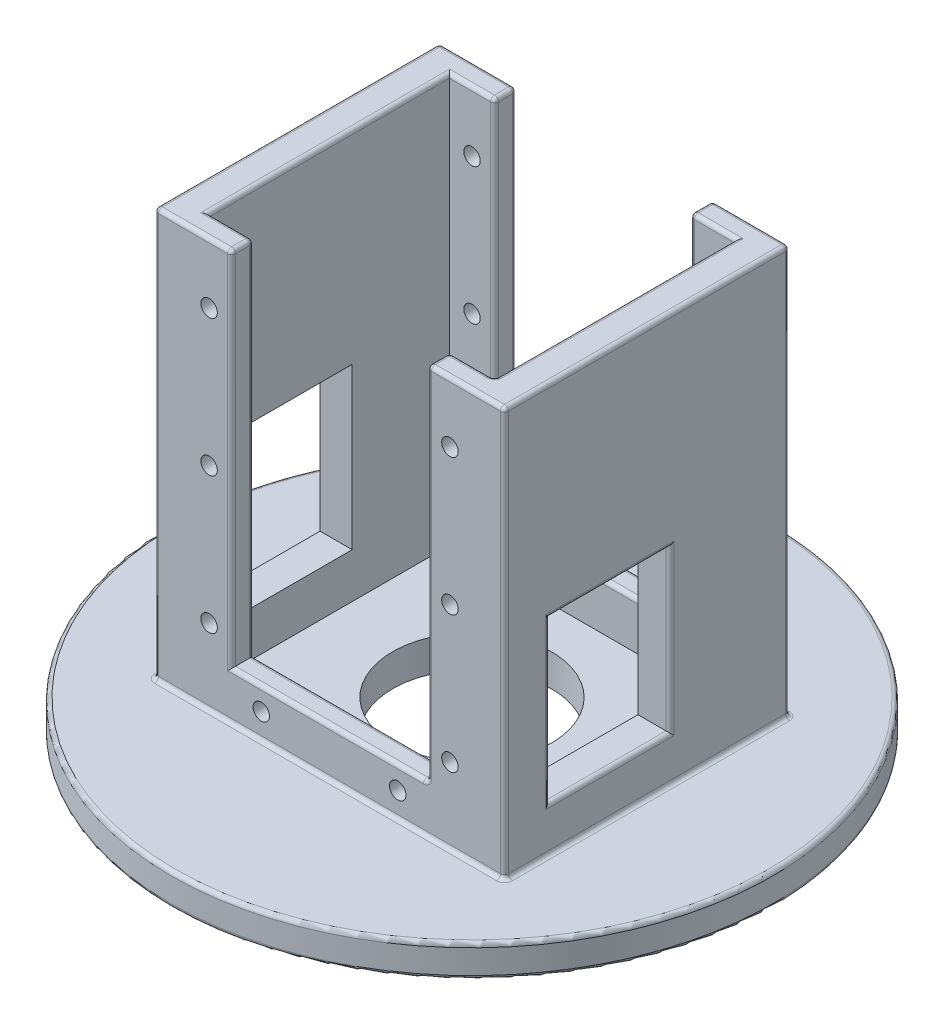
SolidWorks part; units mm, degrees
ref_plane "Front Plane" through (0, 0, 0) normal (0, 0, 1) x (1, 0, 0)
ref_plane "Top Plane" through (0, 0, 0) normal (0, 1, 0) x (1, 0, 0)
ref_plane "Right Plane" through (0, 0, 0) normal (1, 0, 0) x (0, 0, -1)
sketch "Sketch1" plane through (0, -34.7869, 0) normal (0, 1, 0) x (1, 0, 0)
  circle A0 centre (0, 0) radius 37.5
  dimension "D1" = 75
extrude "Boss-Extrude1" add sketch "Sketch1" along normal blind 4
sketch "Sketch2" plane through (-36.0045, -30.7869, 0) normal (0, 1, 0) x (1, 0, 0)
  circle A9 centre (36.0045, 0) radius 9.8792
extrude "Cut-Extrude1" cut sketch "Sketch2" against normal through all
ref_plane "Plane1" through (17.8, 0, 0) normal (1, 0, 0) x (0, 0, -1)
sketch "Sketch3" plane through (17.8, 0, 0) normal (1, 0, 0) x (0, 0, -1)
  line L0 (-17.25, 20.104) -> (-14.5, 20.104) construction
  line L1 (-15, 20.104) -> (15, 20.104)
  line L2 (-15, 20.104) -> (-15, -30.7869)
  line L3 (-15, -30.7869) -> (15, -30.7869)
  line L4 (15, 20.104) -> (15, -30.7869)
  line L5 (37.5, -30.7869) -> (-37.5, -30.7869) construction
  line L6 (15, -30.496) -> (15, -29.4389) construction
  line L7 (-15, 19.604) -> (-15, 18.7231) construction
extrude "Boss-Extrude2" add sketch "Sketch3" along normal blind 4
sketch "Sketch4" plane through (21.8, 0, 0) normal (1, 0, 0) x (0, 0, -1)
  line L0 (37.5, -30.7869) -> (-37.5, -30.7869) construction
  line L1 (-15, 20.104) -> (-17.75, 20.104)
  line L2 (-15, 20.104) -> (-15, -30.7869)
  line L3 (-15, -30.7869) -> (-17.75, -30.7869)
  line L4 (-17.75, 20.104) -> (-17.75, -30.7869)
  line L5 (-17.75, -21.896) -> (-17.75, 17.104) construction
  line L7 (15, 20.104) -> (17.75, 20.104)
  line L8 (15, 20.104) -> (15, -30.7869)
  line L9 (15, -30.7869) -> (17.75, -30.7869)
  line L10 (17.75, 20.104) -> (17.75, -30.7869)
  line L11 (15, -30.7869) -> (15, 20.104) construction
  line L12 (15, 20.104) -> (-15, 20.104) construction
  line L13 (-15, -30.7869) -> (15, -30.7869) construction
  line L14 (17.75, 13.603) -> (17.75, -18.395) construction
extrude "Boss-Extrude3" add sketch "Sketch4" against normal up to surface (9.6 mm away)
ref_plane "Plane2" through (-17.8, 0, 0) normal (-1, 0, 0) x (0, 0, 1)
sketch "Sketch5" plane through (-17.8, 0, 0) normal (-1, 0, 0) x (0, 0, 1)
  line L1 (-15, 20.104) -> (15, 20.104)
  line L2 (-15, 20.104) -> (-15, -30.7869)
  line L3 (-15, -30.7869) -> (15, -30.7869)
  line L4 (15, 20.104) -> (15, -30.7869)
extrude "Boss-Extrude4" add sketch "Sketch5" along normal blind 4
sketch "Sketch6" plane through (-21.8, 0, 0) normal (-1, 0, 0) x (0, 0, 1)
  line L1 (-15, 20.104) -> (-17.75, 20.104)
  line L2 (-15, 20.104) -> (-15, -30.7869)
  line L3 (-15, -30.7869) -> (-17.75, -30.7869)
  line L4 (-17.75, 20.104) -> (-17.75, -30.7869)
  line L5 (15, 20.104) -> (17.75, 20.104)
  line L6 (15, 20.104) -> (15, -30.7869)
  line L7 (15, -30.7869) -> (17.75, -30.7869)
  line L8 (17.75, 20.104) -> (17.75, -30.7869)
extrude "Boss-Extrude5" add sketch "Sketch6" against normal up to surface (9.6 mm away)
sketch "Sketch7" plane through (-36.0045, -30.7869, 0) normal (0, 1, 0) x (1, 0, 0)
  line L1 (48.2045, -15) -> (23.8045, -15)
  line L2 (48.2045, -15) -> (48.2045, -17.75)
  line L3 (48.2045, -17.75) -> (23.8045, -17.75)
  line L4 (23.8045, -15) -> (23.8045, -17.75)
  line L5 (23.8045, 15) -> (48.2045, 15)
  line L6 (23.8045, 15) -> (23.8045, 17.75)
  line L7 (23.8045, 17.75) -> (48.2045, 17.75)
  line L8 (48.2045, 15) -> (48.2045, 17.75)
extrude "Boss-Extrude6" add sketch "Sketch7" along normal up to surface (5.8909 mm away)
sketch "Sketch9" plane through (0, 0, 17.75) normal (0, 0, 1) x (1, 0, 0)
  circle A0 centre (-15, 12.604) radius 1.025
  circle A1 centre (-15, -4.396) radius 1.025
  circle A2 centre (-15, -21.396) radius 1.025
  circle A3 centre (-8.5, -27.696) radius 1.025
  circle A4 centre (8.5, -27.696) radius 1.025
  circle A5 centre (15, -21.396) radius 1.025
  circle A6 centre (15, -4.396) radius 1.025
  circle A7 centre (15, 12.604) radius 1.025
extrude "Cut-Extrude2" cut sketch "Sketch9" against normal through all
sketch "Sketch10" plane through (21.8, 0, 0) normal (1, 0, 0) x (0, 0, -1)
  line L1 (-12.1275, -5.1869) -> (2.8725, -5.1869)
  line L2 (-12.1275, -5.1869) -> (-12.1275, -25.1869)
  line L3 (-12.1275, -25.1869) -> (2.8725, -25.1869)
  line L4 (2.8725, -5.1869) -> (2.8725, -25.1869)
  dimension "D1" = 15
  dimension "D2" = 20
extrude "Cut-Extrude3" cut sketch "Sketch10" against normal through all
fillet "Fillet1" radius 0.5 46 edges at (0, -24.896, -15) (0, -24.896, 15) (0, -24.896, 17.75) (0, -30.7869, -17.75) (-12.2, -2.396, -15) (-12.2, -2.396, -17.75) (-12.2, -24.896, -16.375) (-15, 20.104, 15) (-12.2, 20.104, 16.375) (-17, 20.104, 17.75) (-17, 20.104, -17.75) (-12.2, 20.104, -16.375) (-15, 20.104, -15) (-17.8, 20.104, 0) (-21.8, -5.3414, 17.75) (-21.8, -30.7869, 0) (21.8, -30.7869, 0) (-21.8, -5.3414, -17.75) (21.8, 20.104, 0) (-21.8, 20.104, 0) (12.2, -2.396, -17.75) (12.2, -2.396, -15) (12.2, -24.896, -16.375) (12.2, -2.396, 15) (12.2, -2.396, 17.75) (12.2, -24.896, 16.375) (15, 20.104, -15) (12.2, 20.104, -16.375) (17, 20.104, -17.75) (17, 20.104, 17.75) (12.2, 20.104, 16.375) (15, 20.104, 15) (17.8, 20.104, 0) (21.8, -5.3414, -17.75) (21.8, -5.3414, 17.75) (21.8, -25.1869, 4.6275) (21.8, -15.1869, -2.8725) (21.8, -5.1869, 4.6275) (21.8, -15.1869, 12.1275) (0, -30.7869, 37.5) (-12.2, -2.396, 15) (-12.2, -2.396, 17.75) (0, -24.896, -17.75) (0, -34.7869, 37.5) (17.8, -5.3414, 15) (0, -30.7869, 17.75)
